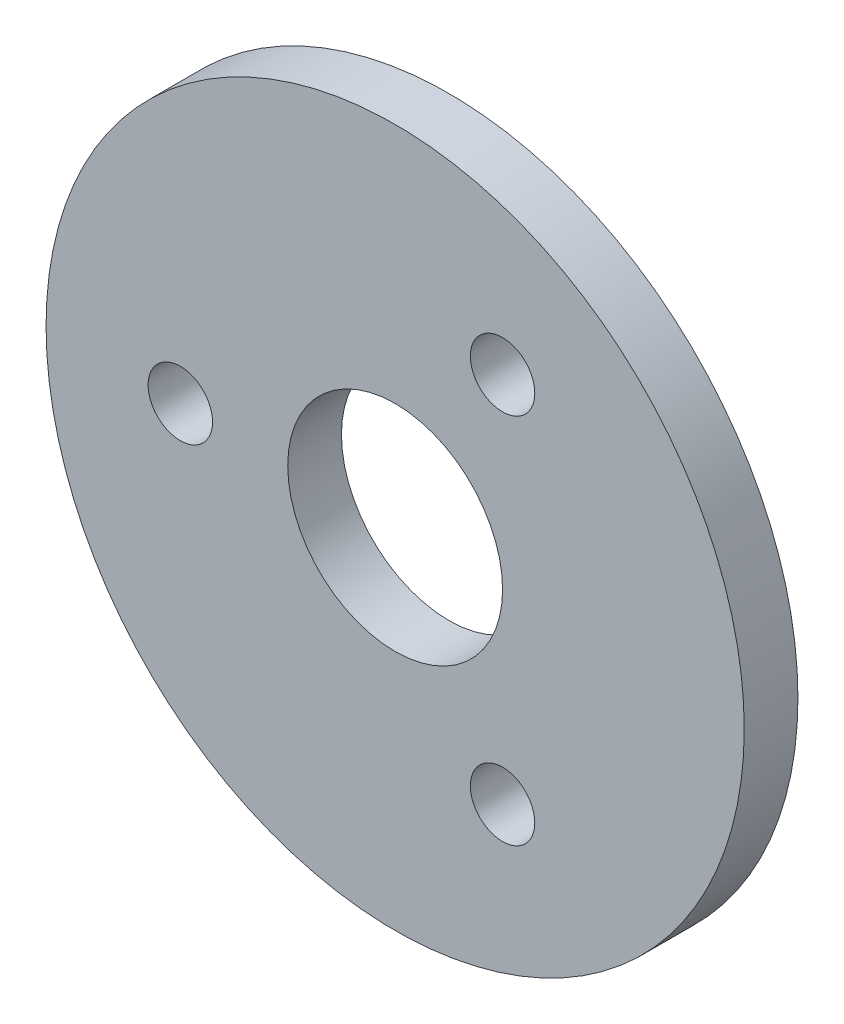
SolidWorks part; units mm, degrees
ref_plane "Front Plane" through (0, 0, 0) normal (1, 0, 0) x (0, 1, 0)
ref_plane "Top Plane" through (0, 0, 0) normal (0, 0, 1) x (0, 1, 0)
ref_plane "Right Plane" through (0, 0, 0) normal (0, 1, 0) x (-1, 0, 0)
sketch "Sketch1" plane through (0, 0, 0) normal (0, 0, 1) x (0, 1, 0)
  circle A0 centre (0, 0) radius 10
  circle A1 centre (0, 0) radius 20 construction
  circle A2 centre (0, 0) radius 32.5
  circle A3 centre (0, 20) radius 3
  circle A4 centre (17.3205, -10) radius 3
  circle A5 centre (-17.3205, -10) radius 3
  point P13 (0, 0)
  dimension "D1" = 20
  dimension "D2" = 40
  dimension "D3" = 65
  dimension "D4" = 6
  dimension "D5" = 3
extrude "Boss-Extrude1" add sketch "Sketch1" along normal mid plane 5
sketch "Sketch3" plane through (0, 0, 0) normal (0, 1, 0) x (-1, 0, 0)
  line L3 (0, 2.5) -> (-32.5, 2.5) construction
  line L6 (10, 2.5) -> (-10, 2.5) construction
